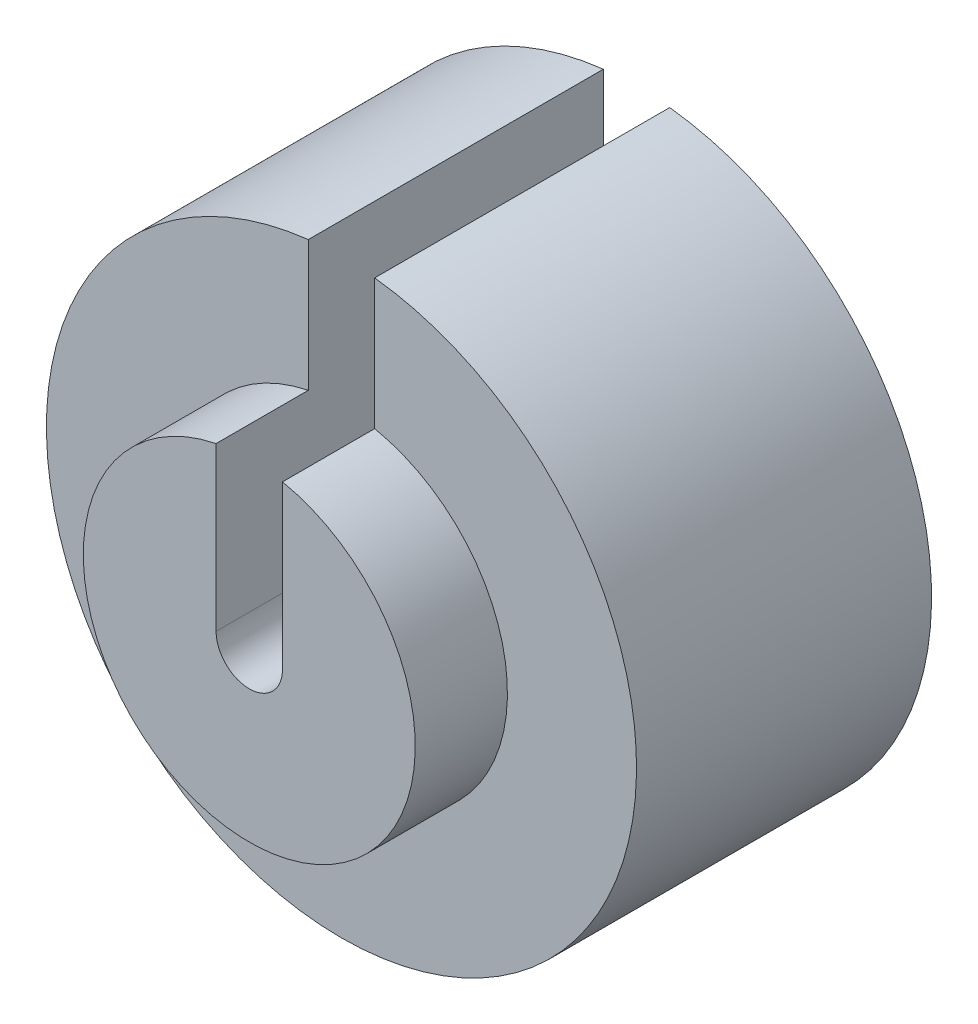
SolidWorks part; units mm, degrees
ref_plane "Front Plane" through (0, 0, 0) normal (0, 0, 1) x (1, 0, 0)
ref_plane "Top Plane" through (0, 0, 0) normal (0, 1, 0) x (1, 0, 0)
ref_plane "Right Plane" through (0, 0, 0) normal (1, 0, 0) x (0, 0, -1)
sketch "Sketch1" plane through (0, 0, 0) normal (0, 0, 1) x (1, 0, 0)
  circle A0 centre (0, 0) radius 0.4
  point P0 (0, 0)
extrude "Boss-Extrude1" add sketch "Sketch1" along normal blind 0.4
sketch "Sketch2" plane through (0, 0, 0) normal (0, 0, -1) x (-1, 0, 0)
  circle A0 centre (0, 0) radius 0.225
extrude "Boss-Extrude2" add sketch "Sketch2" against normal blind 0.525
sketch "Sketch3" plane through (0, 0, 0) normal (0, 0, 1) x (1, 0, 0)
  circle A0 centre (0, 0) radius 0.045
extrude "Cut-Extrude1" cut sketch "Sketch3" along normal through all
sketch "Sketch5" plane through (0, 0, 0) normal (0, 0, -1) x (-1, 0, 0)
  line L1 (0.045, 0) -> (-0.045, 0)
  line L2 (0.045, 0) -> (0.045, 0.5)
  line L3 (0.045, 0.5) -> (-0.045, 0.5)
  line L4 (-0.045, 0) -> (-0.045, 0.5)
  circle A0 centre (0, 0) radius 0.045 construction
  circle A1 centre (0, 0) radius 0.4 construction
  point P6 (0, -0.4)
  dimension "D1" = 0.5
extrude "Cut-Extrude2" cut sketch "Sketch5" against normal through all
